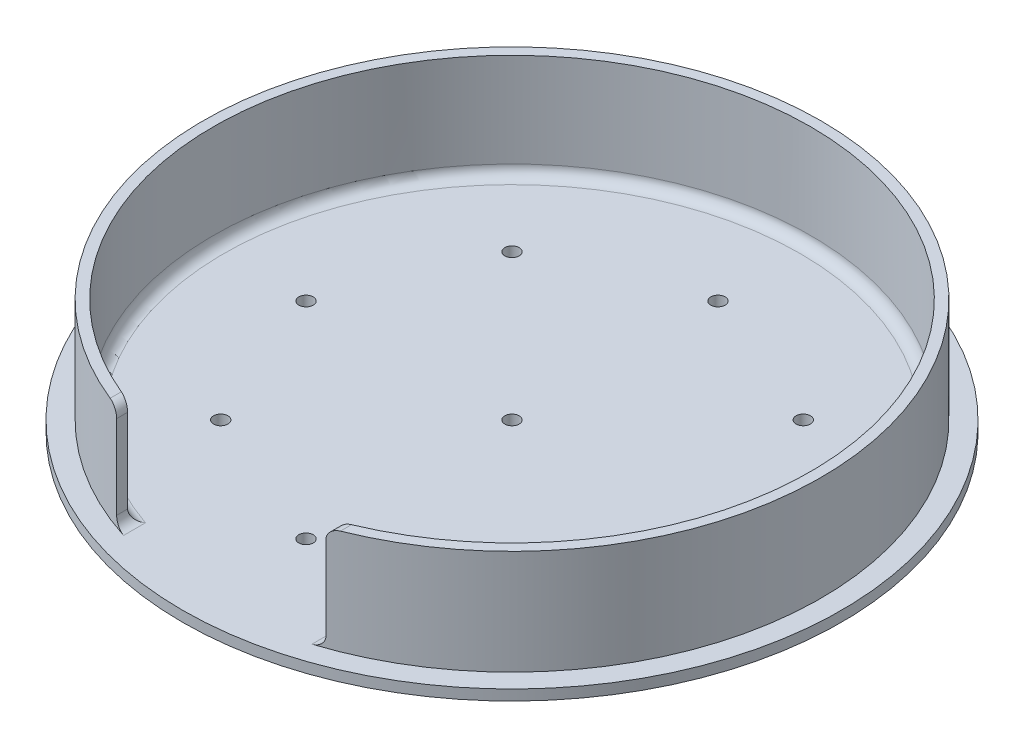
SolidWorks part; units mm, degrees
ref_plane "Front Plane" through (0, 0, 0) normal (0, 0, 1) x (1, 0, 0)
ref_plane "Top Plane" through (0, 0, 0) normal (0, 1, 0) x (1, 0, 0)
ref_plane "Right Plane" through (0, 0, 0) normal (1, 0, 0) x (0, 0, -1)
sketch "Sketch1" plane through (0, 0, 0) normal (0, 1, 0) x (1, 0, 0)
  circle A0 centre (0, 0) radius 80
  dimension "D1" = 160
extrude "Boss-Extrude1" add sketch "Sketch1" along normal blind 2.54
sketch "Sketch2" plane through (0, 2.54, 0) normal (0, 1, 0) x (1, 0, 0)
  circle A0 centre (0, 0) radius 75
  circle A1 centre (0, 0) radius 72.5
  dimension "D1" = 150
  dimension "D2" = 145
extrude "Boss-Extrude2" add sketch "Sketch2" along normal blind 25.4
sketch "Sketch3" plane through (0, 2.54, 0) normal (0, 1, 0) x (1, 0, 0)
  line L0 (0, 0) -> (35.3553, 35.3553) construction
  line L1 (0, 0) -> (35.3553, -35.3553) construction
  line L2 (0, 0) -> (-35.3553, -35.3553) construction
  line L3 (0, 0) -> (-35.3553, 35.3553) construction
  line L4 (0, 0) -> (0, 50) construction
  circle A0 centre (0, 0) radius 50 construction
  circle A1 centre (0, 50) radius 1.75
  circle A2 centre (50, 0) radius 1.75
  circle A3 centre (0, -50) radius 1.75
  circle A4 centre (-50, 0) radius 1.75
  circle A5 centre (35.3553, 35.3553) radius 1.75
  circle A6 centre (35.3553, -35.3553) radius 1.75
  circle A7 centre (-35.3553, -35.3553) radius 1.75
  circle A8 centre (-35.3553, 35.3553) radius 1.75
  circle A9 centre (0, 0) radius 1.75
  dimension "D1" = 100
  dimension "D2" = 3.5
  dimension "D3" = 45
extrude "Cut-Extrude1" cut sketch "Sketch3" against normal through all
sketch "Sketch4" plane through (0, 27.94, 0) normal (0, 1, 0) x (1, 0, 0)
  line L0 (0, 0) -> (0, -75) construction
  line L2 (-25.4, -62.3) -> (25.4, -62.3)
  line L3 (-25.4, -62.3) -> (-25.4, -87.7)
  line L4 (-25.4, -87.7) -> (25.4, -87.7)
  line L5 (25.4, -62.3) -> (25.4, -87.7)
  line L6 (-25.4, -62.3) -> (25.4, -87.7) construction
  line L7 (-25.4, -87.7) -> (25.4, -62.3) construction
  circle A0 centre (0, 0) radius 75 construction
  dimension "D1" = 25.4
  dimension "D2" = 50.8
extrude "Cut-Extrude2" cut sketch "Sketch4" against normal up to surface (25.4 mm away) up to face at (0, 2.54, 75)
fillet "Fillet1" radius 2.54 5 edges at (0, 2.54, -72.5) (-25.4, 27.94, 69.2365) (25.4, 27.94, 69.2365) (25.4, 2.54, 69.2365) (-25.4, 2.54, 69.2365)
